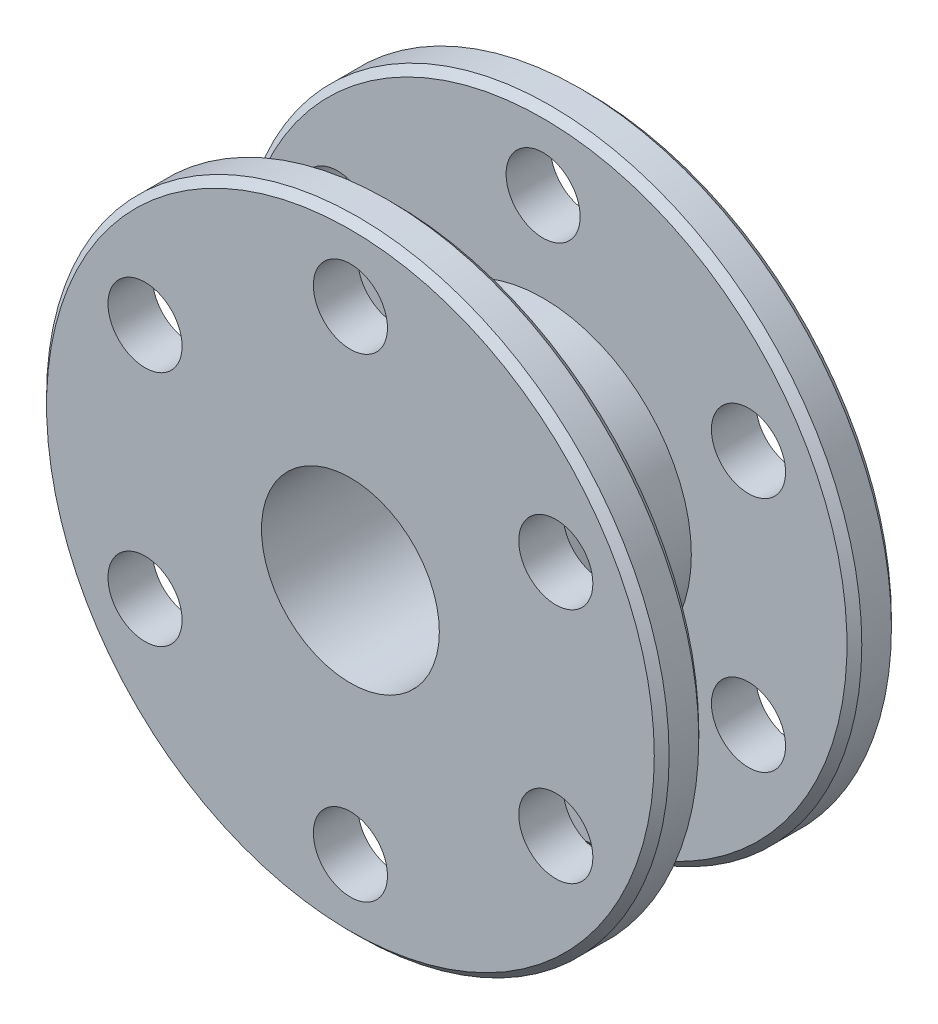
SolidWorks part; units mm, degrees
ref_plane "Front Plane" through (0, 0, 0) normal (0, 0, 1) x (1, 0, 0)
ref_plane "Top Plane" through (0, 0, 0) normal (0, 1, 0) x (1, 0, 0)
ref_plane "Right Plane" through (0, 0, 0) normal (1, 0, 0) x (0, 0, -1)
sketch "Sketch1" plane through (0, 0, 0) normal (0, 0, 1) x (1, 0, 0)
  line L0 (0, 0) -> (0, 22750.0925) construction
  line L1 (0, 0) -> (22750.0925, 0) construction
  circle A0 centre (0, 0) radius 6
  circle A1 centre (0, 0) radius 11.326 construction
  circle A2 centre (0, 0) radius 16 construction
  circle A3 centre (0, 0) radius 21
  circle A4 centre (0, 16) radius 2.5
  circle A5 centre (13.8564, 8) radius 2.5
  circle A6 centre (13.8564, -8) radius 2.5
  circle A7 centre (0, -16) radius 2.5
  circle A8 centre (-13.8564, -8) radius 2.5
  circle A9 centre (-13.8564, 8) radius 2.5
  point P13 (-11.5469, 6.4611)
  point P14 (0, 0)
  point P24 (0, 0)
  dimension "D1" = 32
  dimension "D2" = 12
  dimension "D3" = 22.6519
  dimension "D4" = 42
  dimension "D5" = 5
  dimension "D6" = 6
extrude "Boss-Extrude1" add sketch "Sketch1" along normal blind 16
ref_axis "Axis2" through (0, 0, 16) along (0, 0, -1)
sketch "Sketch3" plane through (0, 0, 0) normal (0, 1, 0) x (1, 0, 0)
  line L0 (21, 0) -> (-21, 0) construction
  line L1 (10, -3) -> (29.705, -3)
  line L2 (10, -3) -> (10, -13)
  line L3 (10, -13) -> (29.705, -13)
  line L4 (29.705, -3) -> (29.705, -13)
  line L5 (-21, -16) -> (21, -16) construction
  dimension "D1" = 10
  dimension "D2" = 19.705
  dimension "D3" = 3
  dimension "D4" = 3
revolve "Cut-Revolve1" cut sketch "Sketch3" angle 360 about axis through (0, 0, 16) along (0, 0, -1)
chamfer "Chamfer1" distance 0.5 angle 45 4 edges at (21, 0, 16) (-21, 0, 3) (21, 0, 13) (21, 0, 0)
